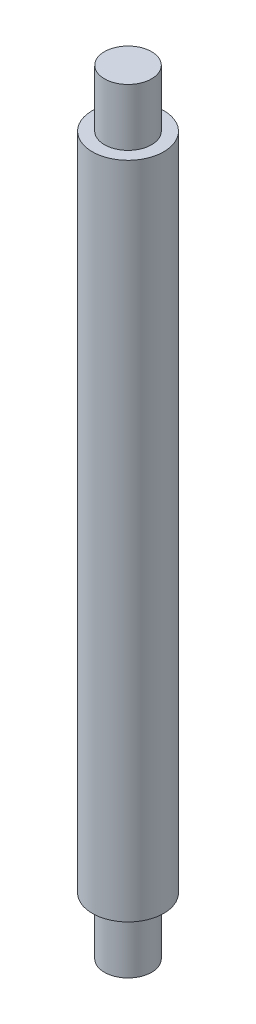
SolidWorks part; units mm, degrees
ref_plane "Front Plane" through (0, 0, 0) normal (0, 0, 1) x (1, 0, 0)
ref_plane "Top Plane" through (0, 0, 0) normal (0, 1, 0) x (1, 0, 0)
ref_plane "Right Plane" through (0, 0, 0) normal (1, 0, 0) x (0, 0, -1)
sketch "Esboço1" plane through (0, 0, 0) normal (0, 1, 0) x (1, 0, 0)
  circle A0 centre (0, 0) radius 5
  dimension "D1" = 10
extrude "Ressalto-extrusão1" add sketch "Esboço1" along normal mid plane 108.4
sketch "Esboço2" plane through (0, 54.2, 0) normal (0, 1, 0) x (1, 0, 0)
  circle A0 centre (0, 0) radius 3.3
  circle A1 centre (0, 0) radius 5
  dimension "D1" = 6.6
  dimension "D2" = 10
extrude "Corte-extrusão1" cut sketch "Esboço2" against normal blind 8
mirror "Espelhar1" about plane through (0, 0, 0) normal (0, 1, 0) of "Corte-extrusão1"
